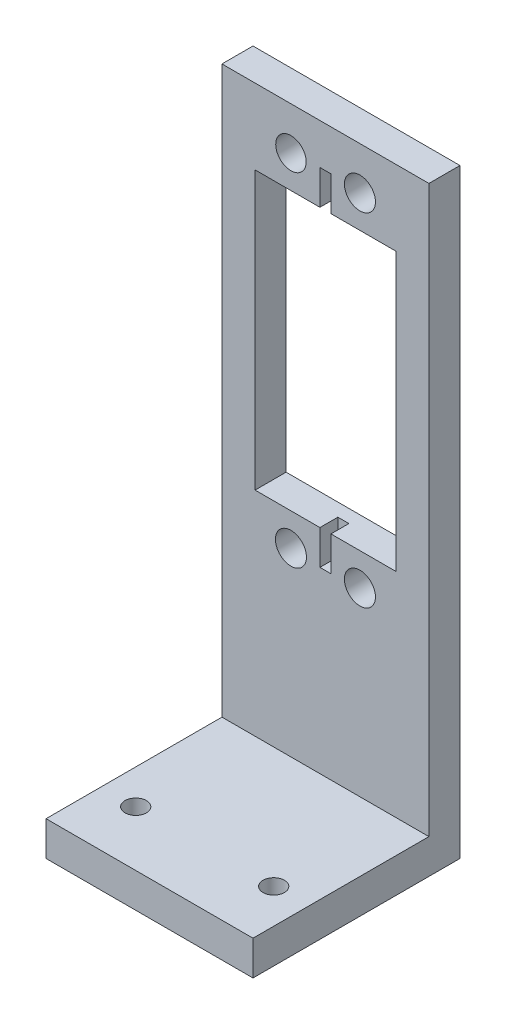
SolidWorks part; units mm, degrees
ref_plane "前视基准面" through (0, 0, 0) normal (0, 0, 1) x (1, 0, 0)
ref_plane "上视基准面" through (0, 0, 0) normal (0, 1, 0) x (1, 0, 0)
ref_plane "右视基准面" through (0, 0, 0) normal (1, 0, 0) x (0, 0, -1)
sketch "草图1" plane through (0, 0, 0) normal (0, 0, 1) x (1, 0, 0)
  line L1 (10.2, -20.1) -> (-10.2, -20.1)
  line L2 (10.2, -20.1) -> (10.2, 20.1)
  line L3 (10.2, 20.1) -> (-10.2, 20.1)
  line L4 (-10.2, -20.1) -> (-10.2, 20.1)
  line L5 (10.2, -20.1) -> (-10.2, 20.1) construction
  line L6 (10.2, 20.1) -> (-10.2, -20.1) construction
  line L7 (15, -31) -> (-15, -31)
  line L8 (15, -31) -> (15, 31)
  line L9 (15, 31) -> (-15, 31)
  line L10 (-15, -31) -> (-15, 31)
  line L11 (15, -31) -> (-15, 31) construction
  line L12 (15, 31) -> (-15, -31) construction
  point P0 (0, 0)
  point P5 (0, 0)
  dimension "D1" = 20.4
  dimension "D2" = 40.2
  dimension "D3" = 30
  dimension "D4" = 62
extrude "凸台-拉伸1" add sketch "草图1" along normal blind 4.5
sketch "草图3" plane through (0, 0, 0) normal (0, 0, -1) x (-1, 0, 0)
  circle A0 centre (-5, -24.8) radius 2.25
  circle A1 centre (5, -24.8) radius 2.25
  circle A2 centre (-5, 24.8) radius 2.25
  circle A3 centre (5, 24.8) radius 2.2065
extrude "切除-拉伸1" cut sketch "草图3" against normal through all
sketch "草图4" plane through (0, 31, 0) normal (0, 1, 0) x (1, 0, 0)
  line L4 (15, 0) -> (-15, 0)
  line L5 (-15, 0) -> (-15, -4.5)
  line L6 (-15, -4.5) -> (15, -4.5)
  line L7 (15, -4.5) -> (15, 0)
  line L8 (15, 0) -> (-15, 0)
  line L9 (-15, 0) -> (-15, -4.5)
  line L10 (-15, -4.5) -> (15, -4.5)
  line L11 (15, -4.5) -> (15, 0)
  dimension "D1" = 0
sketch "草图5" plane through (0, -31, 0) normal (0, -1, 0) x (1, 0, 0)
  line L4 (-15, 0) -> (15, 0)
  line L5 (15, 0) -> (15, 4.5)
  line L6 (15, 4.5) -> (-15, 4.5)
  line L7 (-15, 4.5) -> (-15, 0)
  line L8 (-15, 0) -> (15, 0)
  line L9 (15, 0) -> (15, 4.5)
  line L10 (15, 4.5) -> (-15, 4.5)
  line L11 (-15, 4.5) -> (-15, 0)
  dimension "D1" = 0
extrude "凸台-拉伸3" add sketch "草图5" along normal blind 20
sketch "草图6" plane through (0, -51, 0) normal (0, -1, 0) x (1, 0, 0)
  line L0 (-15, 4.5) -> (-15, 0) construction
  line L1 (15, 0) -> (-15, 0)
  line L2 (15, 0) -> (15, 30)
  line L3 (15, 30) -> (-15, 30)
  line L4 (-15, 0) -> (-15, 30)
  dimension "D1" = 30
extrude "凸台-拉伸4" add sketch "草图6" along normal blind 5
sketch "草图7" plane through (0, -56, 0) normal (0, -1, 0) x (1, 0, 0)
  line L0 (0, 30) -> (0, 22) construction
  line L1 (15, 30) -> (-15, 30) construction
  line L2 (0, 22) -> (10, 22) construction
  circle A0 centre (10, 22) radius 1.55
  circle A1 centre (-10, 22) radius 1.55
  dimension "D1" = 8
  dimension "D3" = 3.1
  dimension "D2" = 10
extrude "切除-拉伸2" cut sketch "草图7" against normal through all
sketch "草图8" plane through (0, 0, 4.5) normal (0, 0, 1) x (1, 0, 0)
  line L0 (0, -20.1) -> (0, -26.5553) construction
  line L1 (-10.2, -20.1) -> (10.2, -20.1) construction
  line L2 (0, 0) -> (13.0244, 0) construction
  line L3 (0.8, 20.1) -> (-0.8, 25.1) construction
  line L4 (0.8, -25.1) -> (-0.8, -25.1)
  line L5 (0.8, -25.1) -> (0.8, -20.1)
  line L6 (0.8, -20.1) -> (-0.8, -20.1)
  line L7 (-0.8, -25.1) -> (-0.8, -20.1)
  line L8 (0.8, -25.1) -> (-0.8, -20.1) construction
  line L9 (0.8, -20.1) -> (-0.8, -25.1) construction
  line L10 (0.8, 25.1) -> (-0.8, 20.1) construction
  line L11 (0, 20.1) -> (0, 26.5553) construction
  line L12 (-0.8, 25.1) -> (-0.8, 20.1)
  line L13 (0.8, 20.1) -> (-0.8, 20.1)
  line L14 (0.8, 25.1) -> (0.8, 20.1)
  line L15 (0.8, 25.1) -> (-0.8, 25.1)
  point P7 (0, -22.6)
  point P18 (0, 22.6)
  dimension "D1" = 1.6
  dimension "D2" = 5
extrude "切除-拉伸3" cut sketch "草图8" against normal blind 2.6
